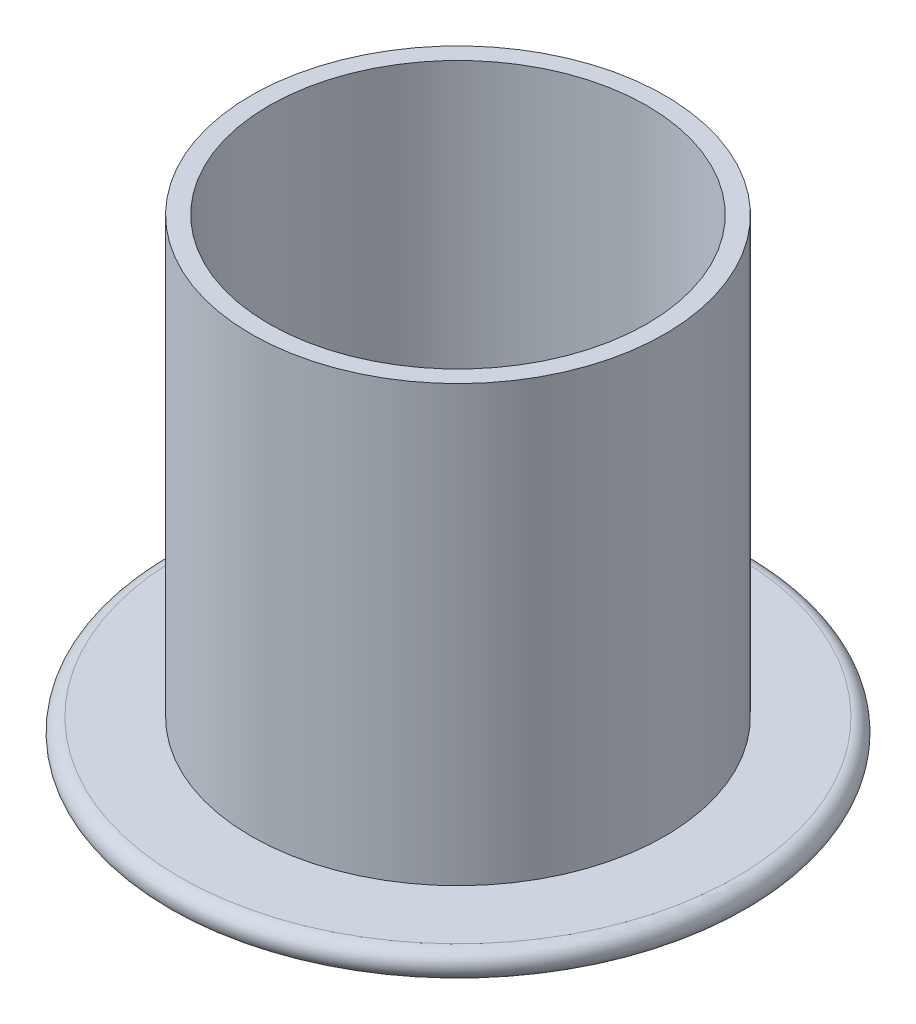
SolidWorks part; units mm, degrees
ref_plane "Front" through (0, 0, 0) normal (0, 0, 1) x (1, 0, 0)
ref_plane "Top" through (0, 0, 0) normal (0, 1, 0) x (1, 0, 0)
ref_plane "Right" through (0, 0, 0) normal (1, 0, 0) x (0, 0, -1)
sketch "Sketch1" plane through (0, 0, 0) normal (0, 0, 1) x (1, 0, 0)
  line L0 (0, 43.6022) -> (0, -30.9113) construction
  line L1 (21.25, 30.1861) -> (23.25, 30.1861)
  line L2 (23.25, 30.1861) -> (23.25, -18.7055)
  line L3 (21.25, 30.1861) -> (21.25, -25.5752)
  line L4 (23.25, -18.7055) -> (31.25, -18.7055)
  line L5 (31.6818, -21.642) -> (25.25, -23.5752)
  line L6 (25.25, -23.5752) -> (25.25, -25.5752)
  line L7 (25.25, -25.5752) -> (21.25, -25.5752)
  arc A0 (31.25, -18.7055) -> (31.6818, -21.642) centre (31.25, -20.2055) cw
  dimension "D4" = 1.5
  dimension "D1" = 21.25
  dimension "D2" = 2
  dimension "D3" = 10
  dimension "D5" = 2
  dimension "D6" = 4
revolve "Revolve1" add sketch "Sketch1" angle 360 about L0
